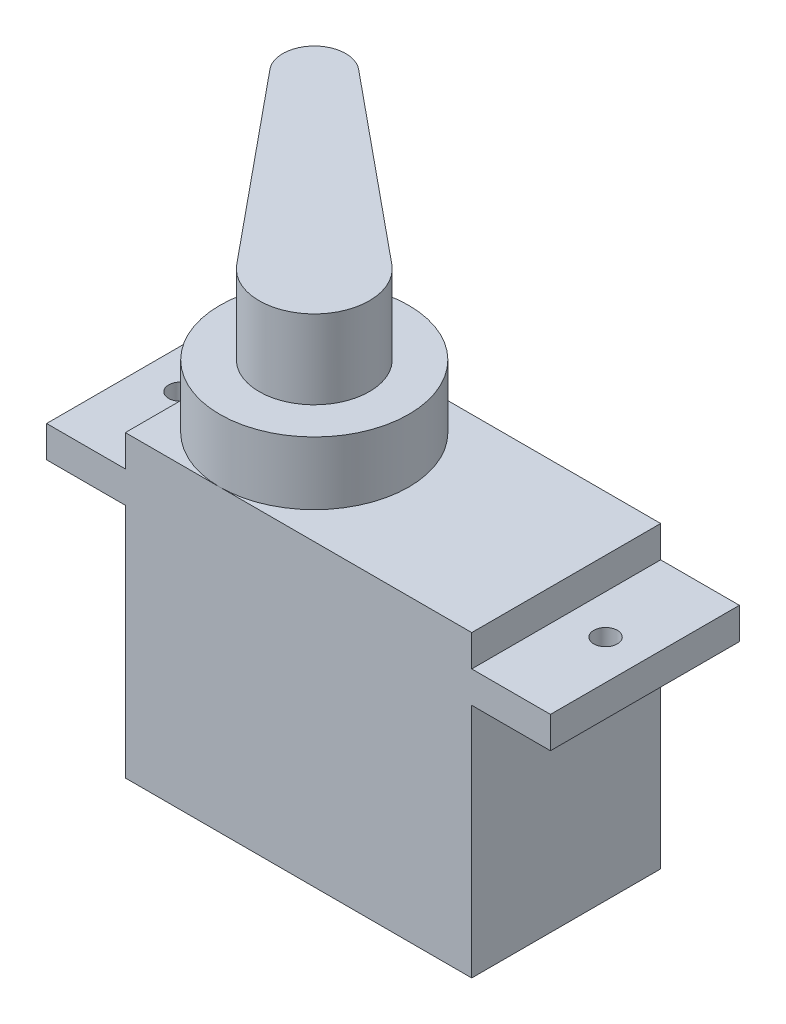
SolidWorks part; units mm, degrees
ref_plane "Front Plane" through (0, 0, 0) normal (0, 0, 1) x (1, 0, 0)
ref_plane "Top Plane" through (0, 0, 0) normal (0, 1, 0) x (1, 0, 0)
ref_plane "Right Plane" through (0, 0, 0) normal (1, 0, 0) x (0, 0, -1)
sketch "Sketch1" plane through (0, 0, 0) normal (0, 1, 0) x (1, 0, 0)
  line L1 (-11, -6) -> (11, -6)
  line L2 (-11, -6) -> (-11, 6)
  line L3 (-11, 6) -> (11, 6)
  line L4 (11, -6) -> (11, 6)
  line L5 (-11, -6) -> (11, 6) construction
  line L6 (-11, 6) -> (11, -6) construction
  point P0 (0, 0)
  dimension "D1" = 12
  dimension "D2" = 22
extrude "Boss-Extrude1" add sketch "Sketch1" along normal blind 15
sketch "Sketch2" plane through (0, 15, 0) normal (0, 1, 0) x (1, 0, 0)
  line L0 (-11, -6) -> (11, -6) construction
  line L1 (-16, -6) -> (16, -6)
  line L2 (-16, -6) -> (-16, 6)
  line L3 (-16, 6) -> (16, 6)
  line L4 (16, -6) -> (16, 6)
  line L5 (-16, -6) -> (16, 6) construction
  line L6 (-16, 6) -> (16, -6) construction
  point P0 (0, 0)
  dimension "D1" = 32
extrude "Boss-Extrude2" add sketch "Sketch2" along normal blind 2
sketch "Sketch4" plane through (0, 17, 0) normal (0, 1, 0) x (1, 0, 0)
  line L0 (-16, -6) -> (16, -6) construction
  line L1 (-11, -6) -> (11, -6)
  line L2 (-11, -6) -> (-11, 6)
  line L3 (-11, 6) -> (11, 6)
  line L4 (11, -6) -> (11, 6)
  line L5 (-11, -6) -> (11, 6) construction
  line L6 (-11, 6) -> (11, -6) construction
  line L7 (11, -6) -> (11, 6) construction
  point P0 (0, 0)
extrude "Boss-Extrude3" add sketch "Sketch4" along normal blind 2
sketch "Sketch5" plane through (0, 19, 0) normal (0, 1, 0) x (1, 0, 0)
  line L0 (-11, 6) -> (-11, -6) construction
  circle A0 centre (-5, 0) radius 6
extrude "Boss-Extrude4" add sketch "Sketch5" along normal blind 4
sketch "Sketch6" plane through (0, 23, 0) normal (0, 1, 0) x (1, 0, 0)
  circle A0 centre (-5, 0) radius 3.5
  dimension "D1" = 7
extrude "Boss-Extrude5" add sketch "Sketch6" along normal blind 5
sketch "Sketch7" plane through (0, 28, 0) normal (0, 1, 0) x (1, 0, 0)
  line L0 (-7.705, -2.221) -> (-17.3943, 9.5794)
  line L1 (-14.5794, 12.3943) -> (-2.779, 2.705)
  line L2 (-7.705, -2.221) -> (-2.779, 2.705) construction
  line L3 (-5.242, 0.242) -> (-15.8486, 10.8486) construction
  line L4 (-5, 0) -> (11, 0) construction
  line L6 (11, -6) -> (11, 6) construction
  circle A0 centre (-5, 0) radius 3.5 construction
  arc A1 (-17.3943, 9.5794) -> (-14.5794, 12.3943) centre (-15.8486, 10.8486) cw
  arc A2 (-7.705, -2.221) -> (-2.779, 2.705) centre (-5, 0) cw
  circle M1 centre (-5, 0) radius 3.5
  dimension "D1" = 2
  dimension "D2" = 15
  dimension "D3" = 135
extrude "Boss-Extrude6" add sketch "Sketch7" against normal blind 2 contours A1 L0 L1 M1
sketch "Sketch8" plane through (0, 17, 0) normal (0, 1, 0) x (1, 0, 0)
  line L0 (-16, 6) -> (-11, -6) construction
  line L1 (11, -6) -> (16, 6) construction
  circle A0 centre (13.5, 0) radius 0.75
  circle A1 centre (-13.5, 0) radius 0.75
  dimension "D1" = 1.5
extrude "Cut-Extrude1" cut sketch "Sketch8" against normal up to next
